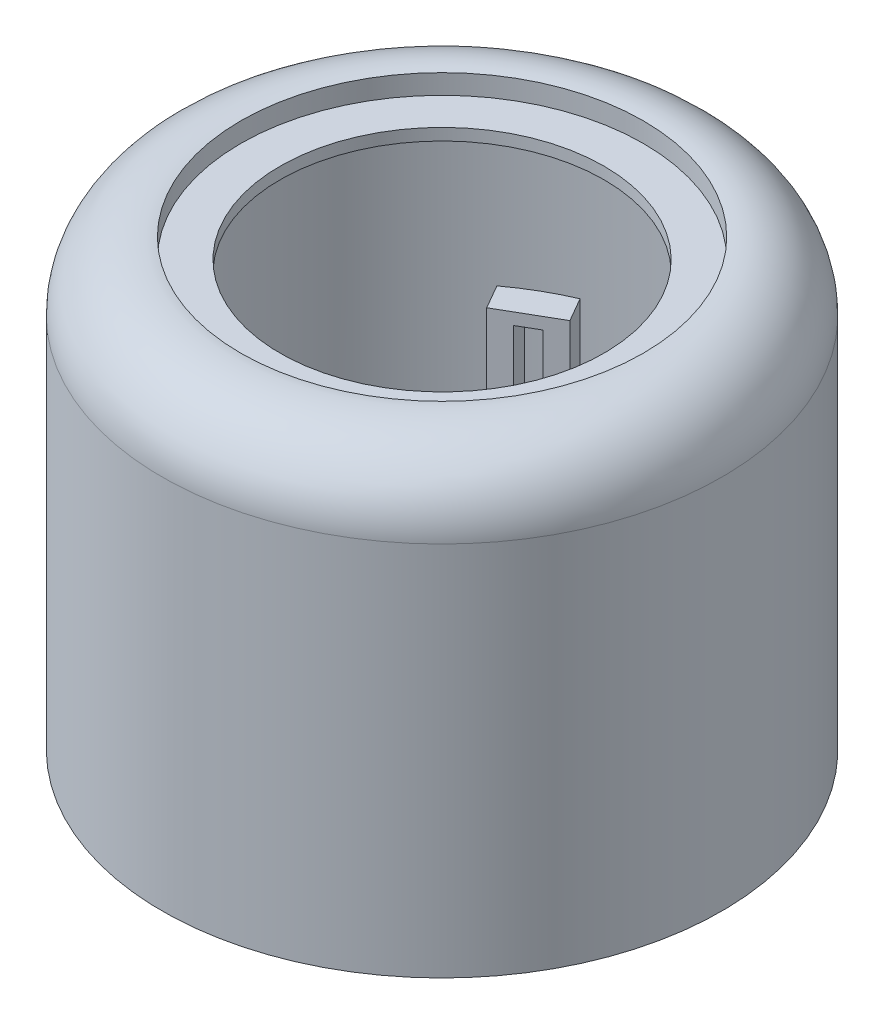
SolidWorks part; units mm, degrees
ref_plane "前视基准面" through (0, 0, 0) normal (0, 0, 1) x (1, 0, 0)
ref_plane "上视基准面" through (0, 0, 0) normal (0, 1, 0) x (1, 0, 0)
ref_plane "右视基准面" through (0, 0, 0) normal (1, 0, 0) x (0, 0, -1)
sketch "草图4" plane through (0, 0, 0) normal (1, 0, 0) x (0, 0, -1)
  line L0 (0, 0) -> (0, 46.8875) construction
  line L1 (16.5, 43.2) -> (16.5, 42)
  line L2 (16.5, 42) -> (22, 42)
  line L3 (27, 37) -> (27, 0)
  line L4 (27, 0) -> (28.5, 0)
  line L5 (28.5, 0) -> (28.5, 38.2718)
  line L7 (20.5, 45.2) -> (20.5, 43.2)
  line L8 (20.5, 43.2) -> (16.5, 43.2)
  arc A0 (28.5, 38.2718) -> (20.5, 45.2) centre (21.5, 38.2718) ccw
  arc A1 (22, 42) -> (27, 37) centre (22, 37) cw
  point P5 (20.5, 44.2)
  point P14 (28, 39.5)
  dimension "D9" = 7
  dimension "D10" = 5
  dimension "D1" = 16.5
  dimension "D2" = 1.2
  dimension "D3" = 2
  dimension "D4" = 20.5
  dimension "D5" = 1.5
  dimension "D6" = 27
  dimension "D7" = 42
revolve "旋转1" add sketch "草图4" angle 360 about L0
sketch "草图5" plane through (0, 0, 0) normal (0, -1, 0) x (1, 0, 0)
  line L0 (0, 0) -> (34.322, 0) construction
  line L1 (28, 3.1) -> (24, 3.1)
  line L2 (28, -1.1) -> (24, -1.1)
  line L3 (28, -1.1) -> (28, -3.1)
  line L4 (28, -3.1) -> (24, -3.1)
  line L5 (24, -1.1) -> (24, -3.1)
  line L6 (24, 1.1) -> (24, 3.1)
  line L7 (28, 1.1) -> (24, 1.1)
  line L8 (28, 1.1) -> (28, 3.1)
  line L9 (16.6847, -22.6987) -> (14.6847, -19.2346)
  line L10 (12.9526, -20.2346) -> (14.6847, -19.2346)
  line L11 (14.9526, -23.6987) -> (12.9526, -20.2346)
  line L12 (14.9526, -23.6987) -> (16.6847, -22.6987)
  line L13 (13.0474, -24.7987) -> (11.3153, -25.7987)
  line L14 (13.0474, -24.7987) -> (11.0474, -21.3346)
  line L15 (11.0474, -21.3346) -> (9.3153, -22.3346)
  line L16 (11.3153, -25.7987) -> (9.3153, -22.3346)
  line L17 (-11.3153, -25.7987) -> (-9.3153, -22.3346)
  line L18 (-11.0474, -21.3346) -> (-9.3153, -22.3346)
  line L19 (-13.0474, -24.7987) -> (-11.0474, -21.3346)
  line L20 (-13.0474, -24.7987) -> (-11.3153, -25.7987)
  line L21 (-14.9526, -23.6987) -> (-16.6847, -22.6987)
  line L22 (-14.9526, -23.6987) -> (-12.9526, -20.2346)
  line L23 (-12.9526, -20.2346) -> (-14.6847, -19.2346)
  line L24 (-16.6847, -22.6987) -> (-14.6847, -19.2346)
  line L25 (-28, -3.1) -> (-24, -3.1)
  line L26 (-24, -1.1) -> (-24, -3.1)
  line L27 (-28, -1.1) -> (-24, -1.1)
  line L28 (-28, -1.1) -> (-28, -3.1)
  line L29 (-28, 1.1) -> (-28, 3.1)
  line L30 (-28, 1.1) -> (-24, 1.1)
  line L31 (-24, 1.1) -> (-24, 3.1)
  line L32 (-28, 3.1) -> (-24, 3.1)
  line L33 (-16.6847, 22.6987) -> (-14.6847, 19.2346)
  line L34 (-12.9526, 20.2346) -> (-14.6847, 19.2346)
  line L35 (-14.9526, 23.6987) -> (-12.9526, 20.2346)
  line L36 (-14.9526, 23.6987) -> (-16.6847, 22.6987)
  line L37 (-13.0474, 24.7987) -> (-11.3153, 25.7987)
  line L38 (-13.0474, 24.7987) -> (-11.0474, 21.3346)
  line L39 (-11.0474, 21.3346) -> (-9.3153, 22.3346)
  line L40 (-11.3153, 25.7987) -> (-9.3153, 22.3346)
  line L41 (11.3153, 25.7987) -> (9.3153, 22.3346)
  line L42 (11.0474, 21.3346) -> (9.3153, 22.3346)
  line L43 (13.0474, 24.7987) -> (11.0474, 21.3346)
  line L44 (13.0474, 24.7987) -> (11.3153, 25.7987)
  line L45 (14.9526, 23.6987) -> (16.6847, 22.6987)
  line L46 (14.9526, 23.6987) -> (12.9526, 20.2346)
  line L47 (12.9526, 20.2346) -> (14.6847, 19.2346)
  line L48 (16.6847, 22.6987) -> (14.6847, 19.2346)
  point P11 (0, 0)
  point P12 (0, 0)
  dimension "D1" = 2.2
  dimension "D2" = 24
  dimension "D3" = 28
  dimension "D4" = 2
  dimension "D5" = 6
extrude "凸台-拉伸1" add sketch "草图5" against normal blind 22
sketch "草图6" plane through (0, 22, 0) normal (0, 1, 0) x (1, 0, 0)
  line L0 (9.3153, -22.3346) -> (11.0653, -25.3657)
  line L1 (24, -3.1) -> (27.5, -3.1)
  line L2 (24, -3.1) -> (24, 3.1)
  line L3 (24, 3.1) -> (27.5, 3.1)
  line L4 (27.5, -3.1) -> (27.5, 3.1)
  line L5 (9.3153, -22.3346) -> (14.6847, -19.2346)
  line L6 (14.6847, -19.2346) -> (16.4347, -22.2657)
  line L7 (11.0653, -25.3657) -> (16.4347, -22.2657)
  line L8 (-14.6847, -19.2346) -> (-16.4347, -22.2657)
  line L9 (-14.6847, -19.2346) -> (-9.3153, -22.3346)
  line L10 (-9.3153, -22.3346) -> (-11.0653, -25.3657)
  line L11 (-16.4347, -22.2657) -> (-11.0653, -25.3657)
  line L12 (-24, 3.1) -> (-27.5, 3.1)
  line L13 (-24, 3.1) -> (-24, -3.1)
  line L14 (-24, -3.1) -> (-27.5, -3.1)
  line L15 (-27.5, 3.1) -> (-27.5, -3.1)
  line L16 (-9.3153, 22.3346) -> (-11.0653, 25.3657)
  line L17 (-9.3153, 22.3346) -> (-14.6847, 19.2346)
  line L18 (-14.6847, 19.2346) -> (-16.4347, 22.2657)
  line L19 (-11.0653, 25.3657) -> (-16.4347, 22.2657)
  line L20 (14.6847, 19.2346) -> (16.4347, 22.2657)
  line L21 (14.6847, 19.2346) -> (9.3153, 22.3346)
  line L22 (9.3153, 22.3346) -> (11.0653, 25.3657)
  line L23 (16.4347, 22.2657) -> (11.0653, 25.3657)
  dimension "D1" = 3.5
  dimension "D2" = 6
extrude "凸台-拉伸2" add sketch "草图6" against normal blind 1.2
sketch "草图7" plane through (0, 0, 0) normal (0, 0, 1) x (1, 0, 0)
  line L0 (-28.5, 0) -> (28.5, 0) construction
  circle A0 centre (0, 12.2) radius 1.4
  dimension "D1" = 2.8
  dimension "D2" = 12.2
extrude "切除-拉伸1" cut sketch "草图7" against normal up to next
